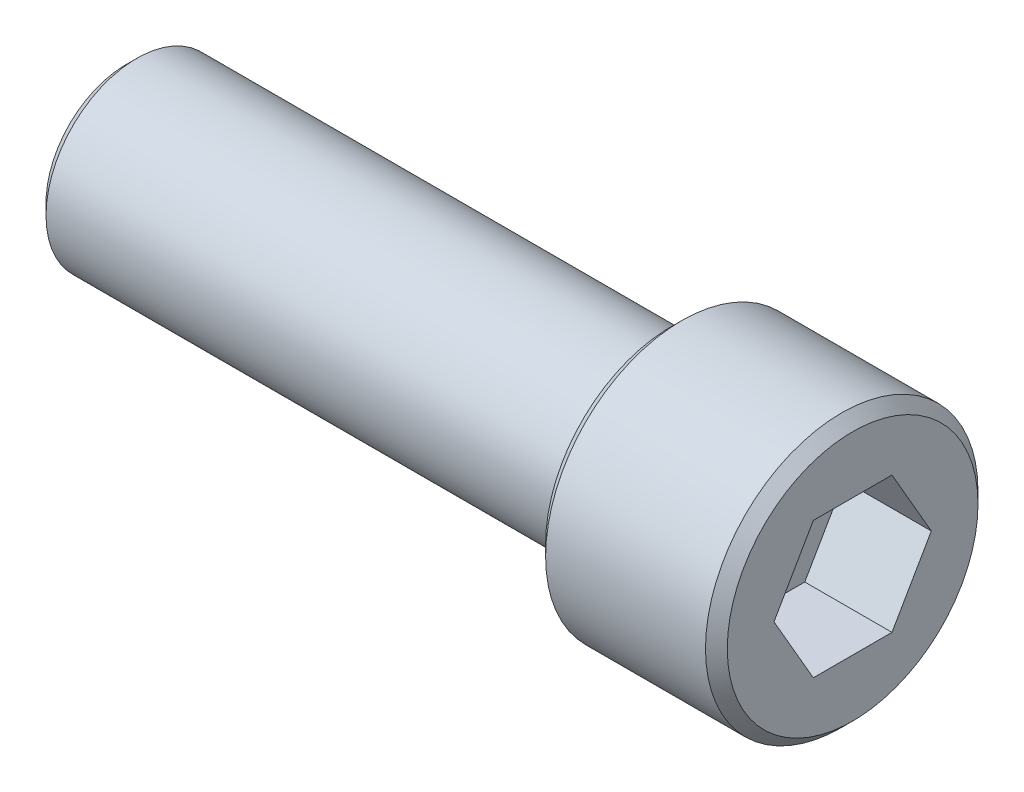
SolidWorks part; units mm, degrees
ref_plane "Front Plane" through (0, 0, 0) normal (0, 0, 1) x (1, 0, 0)
ref_plane "Top Plane" through (0, 0, 0) normal (0, 1, 0) x (1, 0, 0)
ref_plane "Right Plane" through (0, 0, 0) normal (1, 0, 0) x (0, 0, -1)
sketch "Base Sketch" plane through (0, 0, 0) normal (0, 0, 1) x (1, 0, 0)
  line L0 (0, 0) -> (25.4, 0)
  line L1 (25.4, 0) -> (25.4, 4.7625)
  line L2 (25.4, 4.7625) -> (19.05, 4.7625)
  line L3 (19.05, 4.7625) -> (19.05, 3.175)
  line L4 (19.05, 3.175) -> (0, 3.175)
  line L5 (0, 3.175) -> (0, 0)
  line L6 (0, 0) -> (25.4, 0) construction
  line L7 (0, 0) -> (23.0487, 0) construction
  dimension "Screw_Length" = 19.05
  dimension "Head_Height" = 6.35
  dimension "Screw_Diam" = 6.35
  dimension "Head_Diam" = 9.525
revolve "Base" add sketch "Base Sketch" angle 360 about L0
sketch "Hex Sketch" plane through (25.4, 0, 0) normal (1, 0, 0) x (0, 0, -1)
  line L0 (5.2388, 0) -> (-5.2388, 0) construction
  line L1 (-1.3748, 2.3812) -> (-2.7496, 0)
  line L2 (-2.7496, 0) -> (-1.3748, -2.3813)
  line L3 (-1.3748, -2.3813) -> (1.3748, -2.3813)
  line L4 (1.3748, -2.3813) -> (2.7496, 0)
  line L5 (2.7496, 0) -> (1.3748, 2.3813)
  line L6 (1.3748, 2.3813) -> (-1.3748, 2.3812)
  circle A0 centre (0, 0) radius 2.3813 construction
  dimension "Hex_Drive" = 4.7625
extrude "Hex Cut" cut sketch "Hex Sketch" against normal blind 3.048
chamfer "Chamfer2" distance 0.381 angle 45 3 edges at (0, 0, 3.175) (19.05, 0, 4.7625) (25.4, 0, 4.7625)
